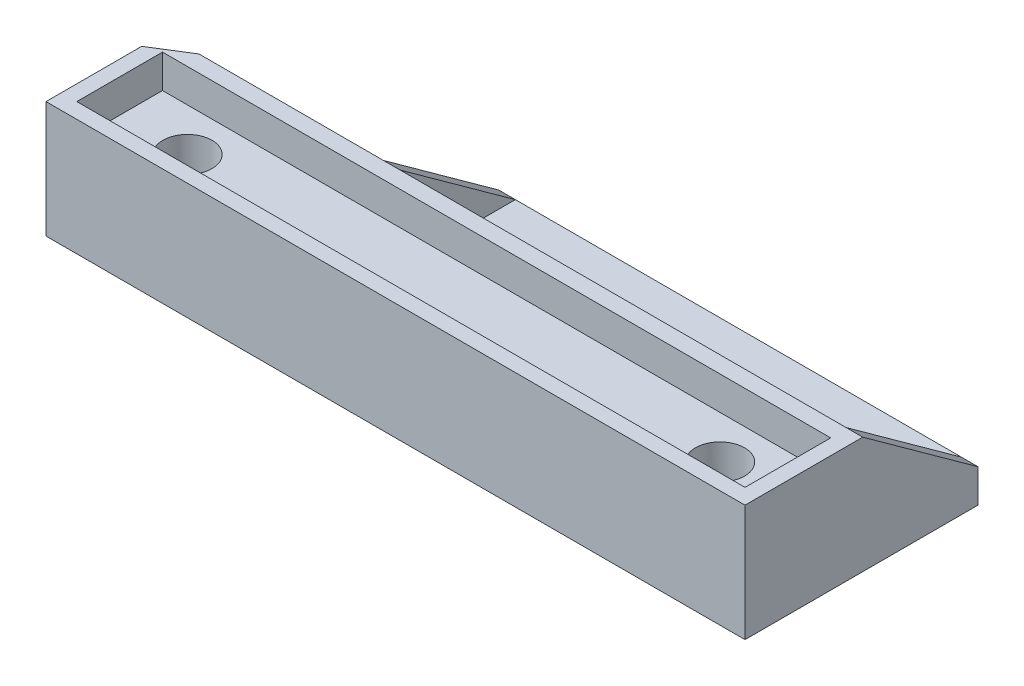
SolidWorks part; units mm, degrees
ref_plane "Front Plane" through (0, 0, 0) normal (0, 0, 1) x (1, 0, 0)
ref_plane "Top Plane" through (0, 0, 0) normal (0, 1, 0) x (1, 0, 0)
ref_plane "Right Plane" through (0, 0, 0) normal (1, 0, 0) x (0, 0, -1)
sketch "Sketch1" plane through (0, 0, 0) normal (0, 1, 0) x (1, 0, 0)
  line L1 (2.0004, 7) -> (42, 7)
  line L2 (0, 5.75) -> (0, 0)
  line L3 (0, 0) -> (42, 0)
  line L4 (42, 7) -> (42, 0)
  line L6 (0, 5.75) -> (2.0004, 7)
  dimension "D1" = 32
  dimension "D2" = 42
  dimension "D3" = 7
  dimension "D4" = 5.75
extrude "Riser" add sketch "Sketch1" along normal blind 7
sketch "Sketch2" plane through (0, 0, 0) normal (0, -1, 0) x (1, 0, 0)
  line L1 (21, 0) -> (21, -7) construction
  line L2 (0, 0) -> (42, 0) construction
  line L4 (42, -7) -> (2.0004, -7) construction
  line L5 (42, 0) -> (42, -7) construction
  circle A0 centre (37, -3.5) radius 1.475
  circle A2 centre (5, -3.5) radius 1.475
  point P6 (42, -3.5)
  dimension "D2" = 2.95
  dimension "D1" = 5
extrude "Mounting Holes" cut sketch "Sketch2" against normal through all
sketch "Sketch3" plane through (0, 7, 0) normal (0, 1, 0) x (1, 0, 0)
  line L5 (42, 7) -> (2.0004, 7) construction
  line L12 (0.925, 6.075) -> (41.075, 6.075)
  line L13 (0.925, 6.075) -> (0.925, 0.925)
  line L14 (0.925, 0.925) -> (41.075, 0.925)
  line L15 (41.075, 6.075) -> (41.075, 0.925)
  line L16 (42, 0) -> (42, 7) construction
  dimension "D1" = 5.15
  dimension "D2" = 40.15
  dimension "D3" = 0.925
  dimension "D4" = 0.925
extrude "Recess" cut sketch "Sketch3" against normal blind 2 contours L12 L15 L14 L13
sketch "Sketch4" plane through (0, 0, 0) normal (0, 1, 0) x (1, 0, 0)
  line L0 (-7.0926, 1.318) -> (28.8348, 23.768) construction
  line L1 (2.0004, 7) -> (42, 7)
  line L2 (42, 7) -> (42, 14)
  line L3 (42, 14) -> (13.2028, 14)
  line L4 (13.2028, 14) -> (2.0004, 7)
  dimension "D1" = 32
  dimension "D2" = 7
extrude "Flange" add sketch "Sketch4" along normal blind 7
sketch "Sketch5" plane through (0, 7, 0) normal (0, 1, 0) x (1, 0, 0)
  line L0 (14.2028, 7.075) -> (14.2028, 14)
  line L1 (42, 14) -> (13.2028, 14) construction
  line L2 (14.2028, 14) -> (41, 14)
  line L3 (41, 14) -> (41, 7.075)
  line L4 (41, 7.075) -> (14.2028, 7.075)
  line L5 (2.1204, 7.075) -> (13.2028, 7.075)
  line L6 (0.925, 6.075) -> (41.075, 6.075) construction
  line L7 (42, 0) -> (42, 14) construction
  line L8 (13.2028, 14) -> (0, 5.75) construction
  line L9 (13.2028, 7.075) -> (13.2028, 14)
  line L10 (13.2028, 14) -> (2.1204, 7.075)
  dimension "D2" = 1
  dimension "D3" = 1
  dimension "D4" = 1
extrude "Flange Cutout" cut sketch "Sketch5" against normal blind 5
sketch "Sketch7" plane through (41, 0, 0) normal (-1, 0, 0) x (0, 0, 1)
  line L0 (-7.075, 7) -> (-14, 2)
  line L1 (-14, 2) -> (-14, 7)
  line L2 (-14, 7) -> (-7.075, 7)
extrude "Angle Cutout" cut sketch "Sketch7" against normal through all and the other way through all
chamfer "Flange Chamfer 1" distance 1 angle 45 1 edges at (27.6014, 2, -7.075)
chamfer "Flange Chamfer 2" distance 1 angle 45 1 edges at (7.6616, 2, -7.075)
